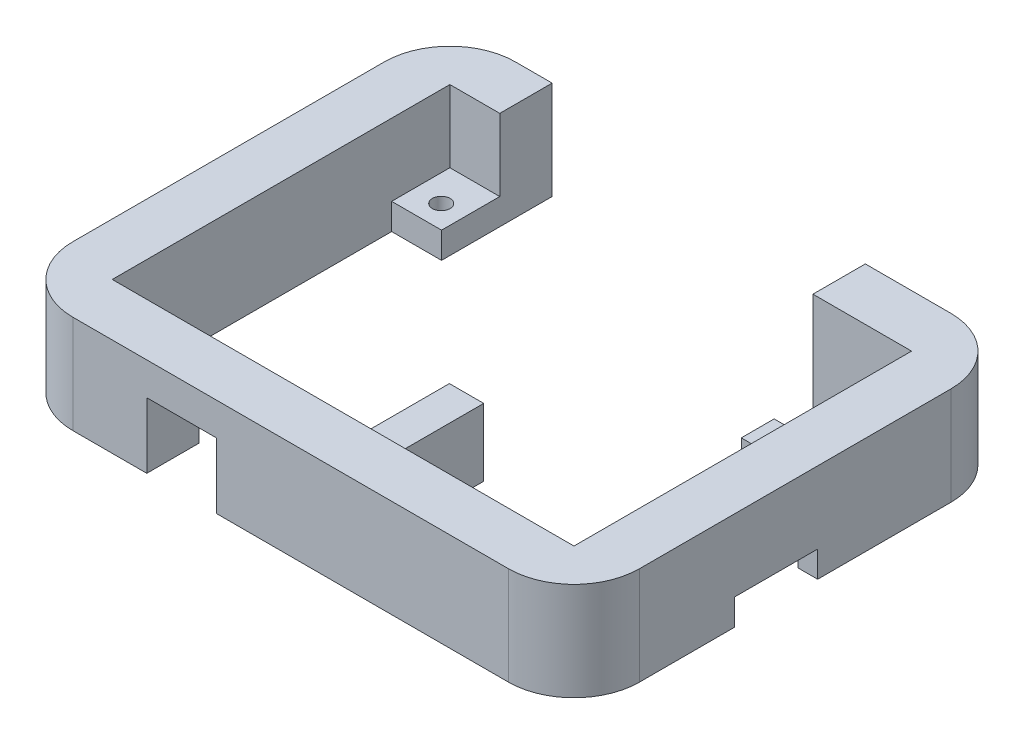
SolidWorks part; units mm, degrees
ref_plane "前视基准面" through (0, 0, 0) normal (0, 0, 1) x (1, 0, 0)
ref_plane "上视基准面" through (0, 0, 0) normal (0, 1, 0) x (1, 0, 0)
ref_plane "右视基准面" through (0, 0, 0) normal (1, 0, 0) x (0, 0, -1)
other "Configuration Table"
sketch "草图2" plane through (0, 0, 0) normal (0, 1, 0) x (1, 0, 0)
  line L1 (-35.25, -25.775) -> (35.25, -25.775)
  line L2 (-35.25, -25.775) -> (-35.25, 25.775)
  line L3 (-35.25, 25.775) -> (35.25, 25.775)
  line L4 (35.25, -25.775) -> (35.25, 25.775)
  line L5 (-35.25, -25.775) -> (35.25, 25.775) construction
  line L6 (-35.25, 25.775) -> (35.25, -25.775) construction
  line L7 (-33.25, -33.775) -> (33.25, -33.775)
  line L8 (-43.25, -23.775) -> (-43.25, 23.775)
  line L9 (-33.25, 33.775) -> (33.25, 33.775)
  line L10 (43.25, -23.775) -> (43.25, 23.775)
  line L11 (-43.25, -33.775) -> (43.25, 33.775) construction
  line L12 (-43.25, 33.775) -> (43.25, -33.775) construction
  arc A0 (-33.25, 33.775) -> (-43.25, 23.775) centre (-33.25, 23.775) ccw
  arc A1 (43.25, 23.775) -> (33.25, 33.775) centre (33.25, 23.775) ccw
  arc A2 (33.25, -33.775) -> (43.25, -23.775) centre (33.25, -23.775) ccw
  arc A3 (-33.25, -33.775) -> (-43.25, -23.775) centre (-33.25, -23.775) cw
  point P0 (0, 0)
  point P6 (0, 0)
  dimension "D5" = 10
  dimension "D6" = 10
  dimension "D1" = 70.5
  dimension "D2" = 51.55
  dimension "D3" = 8
  dimension "D4" = 8
extrude "凸台-拉伸1" add sketch "草图2" along normal blind 15
sketch "草图3" plane through (0, 0, 0) normal (0, 1, 0) x (1, 0, 0)
  line L0 (0, 25.775) -> (0, 0) construction
  line L1 (-35.25, 25.775) -> (-27.63, 25.775)
  line L2 (-35.25, 25.775) -> (-35.25, 16.885)
  line L3 (-35.25, 16.885) -> (-27.63, 16.885)
  line L4 (-27.63, 25.775) -> (-27.63, 16.885)
  line L5 (35.25, 25.775) -> (27.63, 25.775)
  line L6 (35.25, 25.775) -> (35.25, 16.885)
  line L7 (35.25, 16.885) -> (27.63, 16.885)
  line L8 (27.63, 25.775) -> (27.63, 16.885)
  line L9 (35.25, 25.775) -> (-35.25, 25.775) construction
  line L10 (0, 0) -> (-62.0392, 0) construction
  circle A0 centre (-31.18, 20.385) radius 1.35
  circle A1 centre (31.18, 20.385) radius 1.35
  dimension "D5" = 2.7
  dimension "D6" = 20.385
  dimension "D1" = 8.89
  dimension "D4" = 7.62
  dimension "D7" = 62.36
extrude "凸台-拉伸2" add sketch "草图3" along normal blind 4
sketch "草图4" plane through (0, 15, 0) normal (0, 1, 0) x (1, 0, 0)
  line L0 (33.25, 33.775) -> (-33.25, 33.775) construction
  line L1 (-27.63, 33.775) -> (20.1878, 33.775)
  line L2 (-27.63, 33.775) -> (-27.63, 25.775)
  line L3 (-27.63, 25.775) -> (20.1878, 25.775)
  line L4 (20.1878, 33.775) -> (20.1878, 25.775)
  line L5 (35.25, 25.775) -> (-35.25, 25.775) construction
  line L6 (35.25, -25.775) -> (35.25, 25.775) construction
  line L7 (-35.25, 25.775) -> (-35.25, -25.775) construction
  dimension "D1" = 15.0622
  dimension "D2" = 7.62
extrude "切除-拉伸1" cut sketch "草图4" against normal blind 15
sketch "草图5" plane through (0, 0, 0) normal (0, 1, 0) x (1, 0, 0)
  line L0 (-35.25, -25.775) -> (35.25, -25.775) construction
  line L1 (-0.4457, -25.775) -> (4.7969, -25.775)
  line L2 (-0.4457, -25.775) -> (-0.4457, -9.1023)
  line L3 (-0.4457, -9.1023) -> (4.7969, -9.1023)
  line L4 (4.7969, -25.775) -> (4.7969, -9.1023)
  line L5 (35.25, -25.775) -> (35.25, 25.775) construction
  line L11 (35.25, 25.775) -> (20.1878, 25.775) construction
  line L12 (35.25, 11.0191) -> (29.0208, 11.0191)
  line L13 (35.25, 11.0191) -> (35.25, 6)
  line L14 (35.25, 6) -> (29.0208, 6)
  line L15 (29.0208, 11.0191) -> (29.0208, 6)
  line L16 (0, 0) -> (54.4126, 0) construction
  dimension "D1" = 35.6957
  dimension "D2" = 30.4531
  dimension "D3" = 16.6727
  dimension "D4" = 14.7559
  dimension "D5" = 6
  dimension "D6" = 6.2292
extrude "凸台-拉伸3" add sketch "草图5" along normal blind 10.3
sketch "草图7" plane through (0, 0, 0) normal (0, -1, 0) x (1, 0, 0)
  line L5 (35.25, 25.775) -> (35.25, -6) construction
  line L6 (35.25, 9.2679) -> (43.25, 9.2679)
  line L7 (35.25, 9.2679) -> (35.25, -3.4321)
  line L8 (35.25, -3.4321) -> (43.25, -3.4321)
  line L9 (43.25, 9.2679) -> (43.25, -3.4321)
  line L10 (43.25, 23.775) -> (43.25, -23.775) construction
  line L12 (27.25, 2.9179) -> (43.25, 2.9179) construction
  line L13 (27.63, -25.775) -> (20.1878, -25.775) construction
  point P12 (35.25, 2.9179)
  dimension "D1" = 28.6929
  dimension "D2" = 12.7
extrude "切除-拉伸4" cut sketch "草图7" against normal blind 4
ref_plane "基准面2" through (38.05, 0, 0) normal (-1, 0, 0) x (0, 0, 1)
sketch "草图9" plane through (38.05, 0, 0) normal (-1, 0, 0) x (0, 0, 1)
  line L0 (23.775, 0) -> (33.775, 0) construction
  line L1 (-23.775, 8) -> (23.775, 8)
  line L2 (-33.775, 4) -> (-33.775, 0)
  line L3 (-33.775, 0) -> (23.775, 0)
  line L4 (23.775, 8) -> (23.775, 0)
  line L5 (-33.775, 0) -> (-33.775, 15) construction
  line L6 (23.775, 15) -> (23.775, 0) construction
  line L7 (-33.775, 4) -> (-23.775, 4)
  line L8 (-23.775, 4) -> (-23.775, 8)
  line L9 (-23.775, 15) -> (-23.775, 0) construction
  dimension "D1" = 8
  dimension "D2" = 4
extrude "切除-拉伸5" cut sketch "草图9" against normal blind 2.2
sketch "草图11" plane through (0, 0, 0) normal (0, -1, 0) x (-1, 0, 0)
  line L0 (33.25, -33.775) -> (-33.25, -33.775) construction
  line L1 (21.977, -33.775) -> (11.3706, -33.775)
  line L2 (21.977, -33.775) -> (21.977, -25.775)
  line L3 (21.977, -25.775) -> (11.3706, -25.775)
  line L4 (11.3706, -33.775) -> (11.3706, -25.775)
  line L5 (35.25, -25.775) -> (0.4457, -25.775) construction
  line L6 (35.25, 25.775) -> (35.25, -25.775) construction
  dimension "D1" = 13.273
  dimension "D2" = 23.8794
extrude "切除-拉伸6" cut sketch "草图11" against normal blind 10
sketch "草图12" plane through (0, 0, 0) normal (0, -1, 0) x (1, 0, 0)
  line L0 (4.7969, 25.775) -> (35.25, 25.775) construction
  line L1 (8.2731, 28.775) -> (25.2731, 28.775)
  line L2 (8.2731, 28.775) -> (8.2731, 25.775)
  line L3 (8.2731, 25.775) -> (25.2731, 25.775)
  line L4 (25.2731, 28.775) -> (25.2731, 25.775)
  dimension "D1" = 17
  dimension "D2" = 3
extrude "切除-拉伸7" cut sketch "草图12" against normal blind 4
